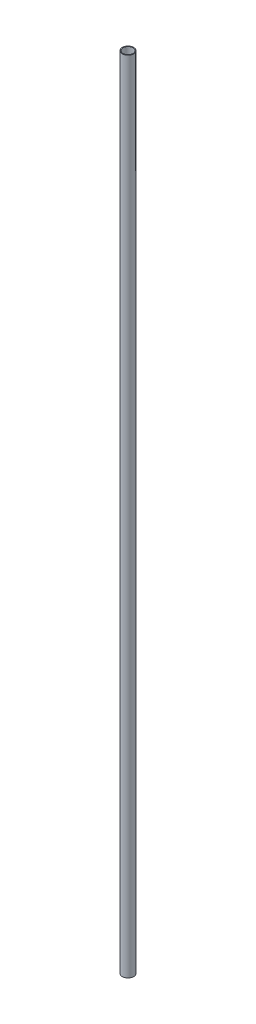
SolidWorks part; units mm, degrees
ref_plane "Piano frontale" through (0, 0, 0) normal (0, 0, 1) x (1, 0, 0)
ref_plane "Piano superiore" through (0, 0, 0) normal (0, 1, 0) x (1, 0, 0)
ref_plane "Piano destro" through (0, 0, 0) normal (1, 0, 0) x (0, 0, -1)
sketch "Schizzo1" plane through (0, 0, 0) normal (0, 1, 0) x (1, 0, 0)
  circle A0 centre (0, 0) radius 7
  circle A1 centre (0, 0) radius 8
  dimension "D1" = 16
  dimension "D2" = 14
extrude "Estrusione-Estrusione1" add sketch "Schizzo1" along normal blind 1130
ref_plane "Piano1" through (0, 5.8, 0) normal (0, 1, 0) x (1, 0, 0)
sketch "Schizzo2" plane through (0, 5.8, 0) normal (0, 1, 0) x (1, 0, 0)
  circle A0 centre (0, 0) radius 8
  dimension "D1" = 16
ref_plane "Piano2" through (0, 17.2, 0) normal (0, 1, 0) x (1, 0, 0)
ref_plane "Piano3" through (0, 34.4, 0) normal (0, 1, 0) x (1, 0, 0)
ref_plane "Piano4" through (0, 57.1, 0) normal (0, 1, 0) x (1, 0, 0)
ref_plane "Piano5" through (0, 85.2, 0) normal (0, 1, 0) x (1, 0, 0)
ref_plane "Piano6" through (0, 118.7, 0) normal (0, 1, 0) x (1, 0, 0)
ref_plane "Piano7" through (0, 157.3, 0) normal (0, 1, 0) x (1, 0, 0)
ref_plane "Piano8" through (0, 200.8, 0) normal (0, 1, 0) x (1, 0, 0)
ref_plane "Piano9" through (0, 249.1, 0) normal (0, 1, 0) x (1, 0, 0)
ref_plane "Piano10" through (0, 301.8, 0) normal (0, 1, 0) x (1, 0, 0)
ref_plane "Piano11" through (0, 358.8, 0) normal (0, 1, 0) x (1, 0, 0)
ref_plane "Piano12" through (0, 419.6, 0) normal (0, 1, 0) x (1, 0, 0)
ref_plane "Piano13" through (0, 484.1, 0) normal (0, 1, 0) x (1, 0, 0)
ref_plane "Piano14" through (0, 551.9, 0) normal (0, 1, 0) x (1, 0, 0)
ref_plane "Piano15" through (0, 622.6, 0) normal (0, 1, 0) x (1, 0, 0)
ref_plane "Piano16" through (0, 695.8, 0) normal (0, 1, 0) x (1, 0, 0)
ref_plane "Piano17" through (0, 771.35, 0) normal (0, 1, 0) x (1, 0, 0)
ref_plane "Piano18" through (0, 848.65, 0) normal (0, 1, 0) x (1, 0, 0)
ref_plane "Piano19" through (0, 927.35, 0) normal (0, 1, 0) x (1, 0, 0)
ref_plane "Piano20" through (0, 1007.05, 0) normal (0, 1, 0) x (1, 0, 0)
ref_plane "Piano21" through (0, 1087.35, 0) normal (0, 1, 0) x (1, 0, 0)
ref_plane "Piano22" through (0, 1127.65, 0) normal (0, 1, 0) x (1, 0, 0)
sketch "Schizzo3" plane through (0, 17.2, 0) normal (0, 1, 0) x (1, 0, 0)
  circle A0 centre (0, 0) radius 8
  dimension "D1" = 16
sketch "Schizzo4" plane through (0, 34.4, 0) normal (0, 1, 0) x (1, 0, 0)
  circle A0 centre (0, 0) radius 8
  dimension "D1" = 16
sketch "Schizzo5" plane through (0, 57.1, 0) normal (0, 1, 0) x (1, 0, 0)
  circle A0 centre (0, 0) radius 8
  dimension "D1" = 16
sketch "Schizzo6" plane through (0, 85.2, 0) normal (0, 1, 0) x (1, 0, 0)
  circle A0 centre (0, 0) radius 8
  dimension "D1" = 16
sketch "Schizzo7" plane through (0, 118.7, 0) normal (0, 1, 0) x (1, 0, 0)
  circle A0 centre (0, 0) radius 8
  dimension "D1" = 16
sketch "Schizzo8" plane through (0, 157.3, 0) normal (0, 1, 0) x (1, 0, 0)
  circle A0 centre (0, 0) radius 8
  dimension "D1" = 16
sketch "Schizzo9" plane through (0, 200.8, 0) normal (0, 1, 0) x (1, 0, 0)
  circle A0 centre (0, 0) radius 8
  dimension "D1" = 16
sketch "Schizzo10" plane through (0, 249.1, 0) normal (0, 1, 0) x (1, 0, 0)
  circle A0 centre (0, 0) radius 8
  dimension "D1" = 16
sketch "Schizzo11" plane through (0, 301.8, 0) normal (0, 1, 0) x (1, 0, 0)
  circle A0 centre (0, 0) radius 8
  dimension "D1" = 16
sketch "Schizzo12" plane through (0, 358.8, 0) normal (0, 1, 0) x (1, 0, 0)
  circle A0 centre (0, 0) radius 8
  dimension "D1" = 16
sketch "Schizzo13" plane through (0, 419.6, 0) normal (0, 1, 0) x (1, 0, 0)
  circle A0 centre (0, 0) radius 8
  dimension "D1" = 16
sketch "Schizzo14" plane through (0, 484.1, 0) normal (0, 1, 0) x (1, 0, 0)
  circle A0 centre (0, 0) radius 8
  dimension "D1" = 16
sketch "Schizzo15" plane through (0, 551.9, 0) normal (0, 1, 0) x (1, 0, 0)
  circle A0 centre (0, 0) radius 8
  dimension "D1" = 16
sketch "Schizzo16" plane through (0, 622.6, 0) normal (0, 1, 0) x (1, 0, 0)
  circle A0 centre (0, 0) radius 8
  dimension "D1" = 16
sketch "Schizzo17" plane through (0, 695.8, 0) normal (0, 1, 0) x (1, 0, 0)
  circle A0 centre (0, 0) radius 8
  dimension "D1" = 16
sketch "Schizzo18" plane through (0, 771.35, 0) normal (0, 1, 0) x (1, 0, 0)
  circle A0 centre (0, 0) radius 8
  dimension "D1" = 16
sketch "Schizzo19" plane through (0, 848.65, 0) normal (0, 1, 0) x (1, 0, 0)
  circle A0 centre (0, 0) radius 8
  dimension "D1" = 16
sketch "Schizzo20" plane through (0, 927.35, 0) normal (0, 1, 0) x (1, 0, 0)
  circle A0 centre (0, 0) radius 8
  dimension "D1" = 16
sketch "Schizzo21" plane through (0, 1007.05, 0) normal (0, 1, 0) x (1, 0, 0)
  circle A0 centre (0, 0) radius 8
  dimension "D1" = 16
sketch "Schizzo22" plane through (0, 1087.35, 0) normal (0, 1, 0) x (1, 0, 0)
  circle A0 centre (0, 0) radius 8
  dimension "D1" = 16
sketch "Schizzo23" plane through (0, 1127.65, 0) normal (0, 1, 0) x (1, 0, 0)
  circle A0 centre (0, 0) radius 8
  dimension "D1" = 16
